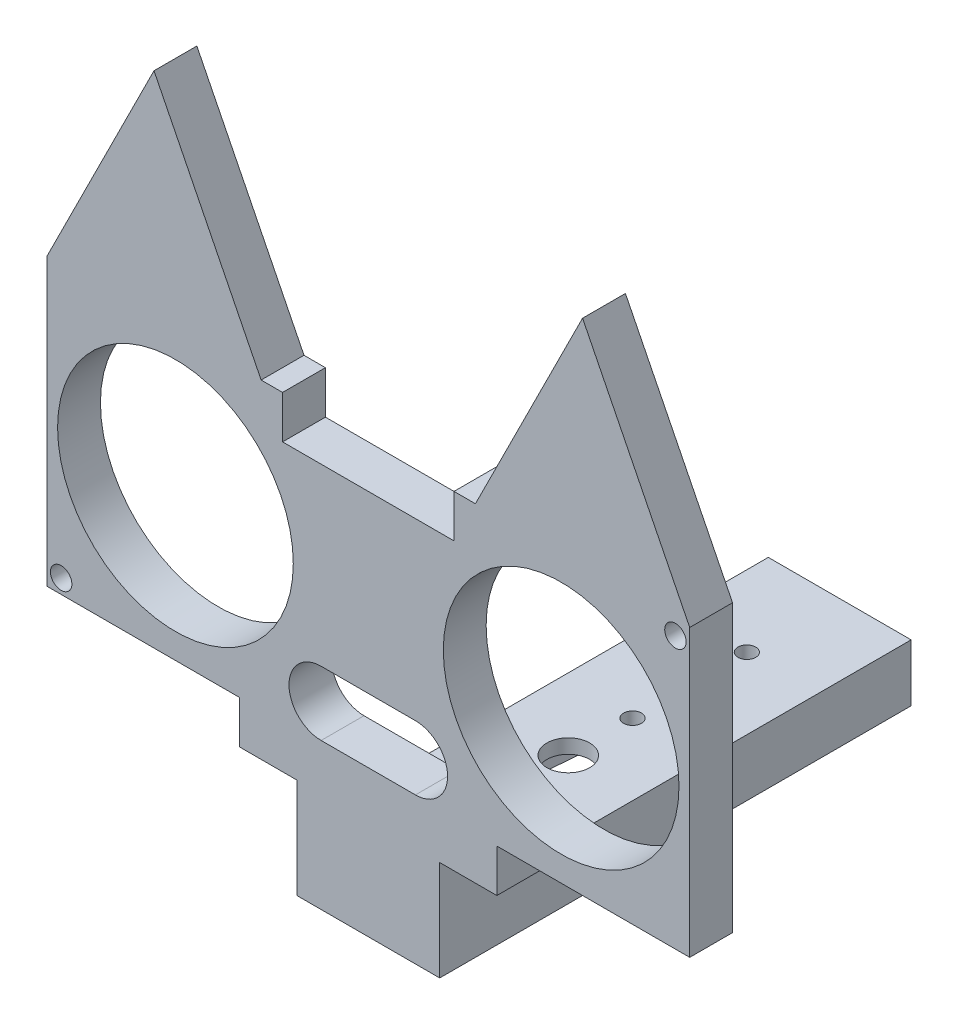
SolidWorks part; units mm, degrees
material "Custom Plastic"
ref_plane "Front Plane" through (0, 0, 0) normal (0, 0, 1) x (1, 0, 0)
ref_plane "Top Plane" through (0, 0, 0) normal (0, 1, 0) x (1, 0, 0)
ref_plane "Right Plane" through (0, 0, 0) normal (1, 0, 0) x (0, 0, -1)
sketch "Sketch1" plane through (0, 0, 0) normal (0, 0, 1) x (1, 0, 0)
  line L0 (0, 10) -> (0, -10) construction
  line L1 (-22.5, -10) -> (22.5, -10)
  line L2 (-22.5, -10) -> (-22.5, 10)
  line L3 (-22.5, 10) -> (22.5, 10)
  line L4 (22.5, -10) -> (22.5, 10)
  line L5 (-22.5, -10) -> (22.5, 10) construction
  line L6 (-22.5, 10) -> (22.5, -10) construction
  point P0 (0, 0)
  dimension "D1" = 45
  dimension "D2" = 20
extrude "Boss-Extrude1" add sketch "Sketch1" along normal blind 3
sketch "Sketch2" plane through (0, 0, 3) normal (0, 0, 1) x (1, 0, 0)
  line L0 (-22.5, 10) -> (-22.5, -10) construction
  line L1 (22.5, 10) -> (-22.5, 10) construction
  line L2 (0, 10) -> (0, -10) construction
  line L3 (-22.5, -10) -> (22.5, -10) construction
  line L4 (22.5, -10) -> (22.5, 10) construction
  circle A0 centre (-13.5, 0) radius 8.25
  circle A2 centre (13.5, 0) radius 8.25
  circle A3 centre (-21.5, -9) radius 0.75
  circle A4 centre (21.5, 9) radius 0.75
  dimension "D2" = 10
  dimension "D3" = 16.5
  dimension "D4" = 1.5
  dimension "D7" = 1.5
  dimension "D1" = 9
  dimension "D5" = 1
  dimension "D6" = 1
  dimension "D8" = 1
  dimension "D9" = 1
extrude "Cut-Extrude1" cut sketch "Sketch2" against normal through all both and the other way through all
sketch "Sketch7" plane through (0, 0, 3) normal (0, 0, 1) x (1, 0, 0)
  line L0 (-22.5, 10) -> (-15, 25)
  line L1 (-15, 25) -> (-7.5, 10)
  line L2 (-7.5, 10) -> (-22.5, 10)
  line L3 (-15, 10) -> (-15, 25) construction
  line L4 (22.5, -10) -> (22.5, 10)
  line L5 (22.5, 10) -> (-22.5, 10)
  line L6 (-22.5, 10) -> (-22.5, -10)
  line L7 (-22.5, -10) -> (22.5, -10)
  line L8 (22.5, -10) -> (22.5, 10)
  line L9 (22.5, 10) -> (-22.5, 10)
  line L10 (-22.5, 10) -> (-22.5, -10)
  line L11 (-22.5, -10) -> (22.5, -10)
  line L12 (0, -1.65) -> (0, 1.65) construction
  line L13 (7.5, 10) -> (22.5, 10)
  line L14 (15, 25) -> (7.5, 10)
  line L15 (22.5, 10) -> (15, 25)
  line M17 (22.5, 10) -> (-22.5, 10)
  dimension "D2" = 15
  dimension "D3" = 15
  dimension "D1" = 0
extrude "Boss-Extrude2" add sketch "Sketch7" against normal up to surface (3 mm away) contours L15 L14 M17 | L3 L1 M17 up to face at (5.25, 0, 0)
sketch "Sketch8" plane through (0, 0, 3) normal (0, 0, 1) x (1, 0, 0)
  line L1 (-22.5, -10) -> (22.5, -10) construction
  line L2 (-5, -13) -> (-5, -20)
  line L3 (-5, -20) -> (5, -20)
  line L4 (5, -20) -> (5, -13)
  line L5 (-5, -13) -> (-9, -13)
  line L6 (-9, -13) -> (-9, -10)
  line L7 (5, -13) -> (9, -13)
  line L8 (9, -13) -> (9, -10)
  line L9 (9, -10) -> (-9, -10)
  point P1 (0, -10)
  point P5 (0, -10)
  dimension "D1" = 4
  dimension "D2" = 3
  dimension "D3" = 10
  dimension "D4" = 7
extrude "Boss-Extrude3" add sketch "Sketch8" against normal up to surface (3 mm away) up to face at (5.25, 0, 0)
sketch "Sketch9" plane through (0, 0, 0) normal (0, 0, -1) x (-1, 0, 0)
  line L0 (-5, -20) -> (5, -20)
  line L1 (5, -20) -> (5, -16)
  line L2 (5, -13) -> (5, -20) construction
  line L3 (5, -16) -> (-5, -16)
  line L4 (-5, -20) -> (-5, -13) construction
  line L5 (-5, -20) -> (-5, -16)
  dimension "D1" = 4
extrude "Boss-Extrude4" add sketch "Sketch9" along normal blind 30
sketch "Sketch10" plane through (0, -20, 0) normal (0, -1, 0) x (1, 0, 0)
  line L1 (-4, -11) -> (-3, -24)
  line L2 (4, -11) -> (3, -24)
  line L3 (5, -30) -> (-5, -30) construction
  arc A0 (-3, -24) -> (3, -24) centre (0, -24) ccw
  arc A1 (4, -11) -> (-4, -11) centre (0, -11) ccw
  point P1 (0, -7)
  point P5 (0, -27)
  dimension "D1" = 20
  dimension "D2" = 4
  dimension "D3" = 3
  dimension "D4" = 3
extrude "Cut-Extrude2" cut sketch "Sketch10" along direction (0, -1, 0) on the side against the normal offset from surface (3 mm away) 1 contours A1 L1 A0 L2
sketch "Sketch11" plane through (0, -16, 0) normal (0, 1, 0) x (1, 0, 0)
  circle A0 centre (0, 11) radius 1.5
  circle A1 centre (0, 15.5) radius 0.625
  circle A2 centre (0, 19.5) radius 0.625
  circle A3 centre (0, 23.5) radius 0.625
  dimension "D1" = 3
  dimension "D3" = 1.25
  dimension "D5" = 1.25
  dimension "D8" = 1.25
  dimension "D2" = 4.5
  dimension "D4" = 4
  dimension "D6" = 4
extrude "Cut-Extrude3" cut sketch "Sketch11" against normal through all both and the other way through all contours A1 | A2 | A0 | A3
sketch "Sketch12" plane through (0, 0, 3) normal (0, 0, 1) x (1, 0, 0)
  line L8 (-3.3, -5.25) -> (3.3, -5.25)
  line L9 (3.3, -9.75) -> (-3.3, -9.75)
  line L10 (-6, 10) -> (-6, 7)
  line L11 (7.5, 10) -> (-7.5, 10) construction
  line L12 (-6, 7) -> (6, 7)
  line L13 (6, 7) -> (6, 10)
  line L14 (-6, 10) -> (6, 10)
  arc A4 (3.3, -5.25) -> (3.3, -9.75) centre (3.3, -7.5) cw
  arc A5 (-3.3, -9.75) -> (-3.3, -5.25) centre (-3.3, -7.5) cw
  point P10 (0, 10)
  point P13 (0, 7)
  dimension "D1" = 12
  dimension "D2" = 3
extrude "Cut-Extrude4" cut sketch "Sketch12" against normal through all both and the other way through all
